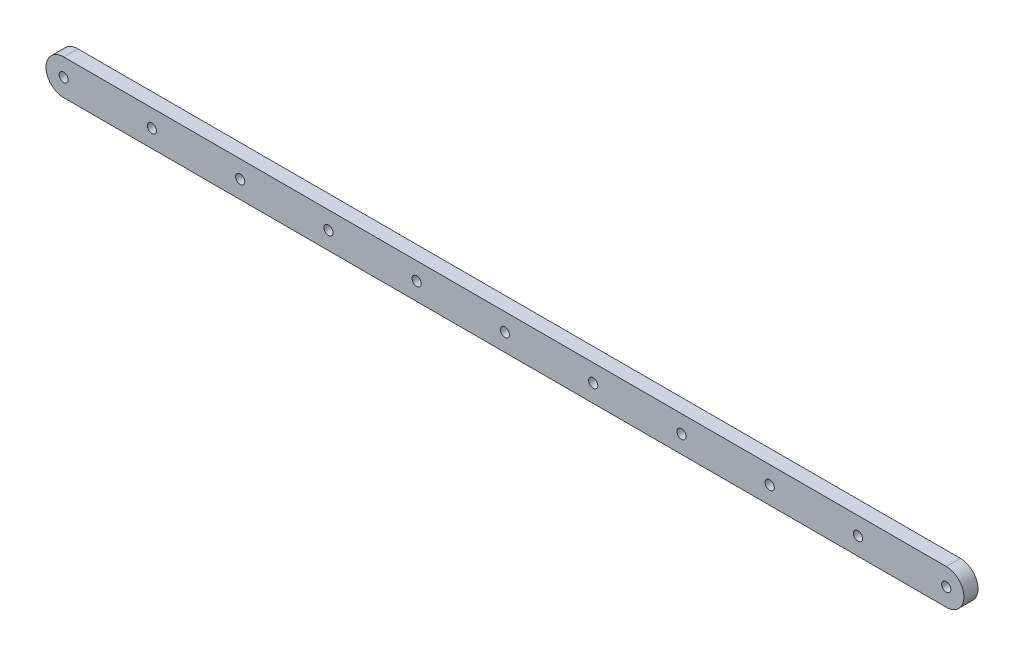
SolidWorks part; units mm, degrees
material "Pine"
ref_plane "Front Plane" through (0, 0, 0) normal (0, 0, 1) x (1, 0, 0)
ref_plane "Top Plane" through (0, 0, 0) normal (0, 1, 0) x (1, 0, 0)
ref_plane "Right Plane" through (0, 0, 0) normal (1, 0, 0) x (0, 0, -1)
sketch "Sketch1" plane through (0, 0, 0) normal (0, 0, 1) x (1, 0, 0)
  line L0 (0, 5) -> (250, 5)
  line L1 (250, -5) -> (0, -5)
  circle A0 centre (0, 0) radius 5
  circle A1 centre (250, 0) radius 5
  dimension "D1" = 250
  dimension "D2" = 10
extrude "Boss-Extrude1" add sketch "Sketch1" along normal blind 4 contours A1 L0 A0 L1 | A1 | A0
ref_plane "Plane1" through (0, 0, 2) normal (0, 0, 1) x (1, 0, 0)
sketch "Sketch2" plane through (0, 0, 4) normal (0, 0, 1) x (1, 0, 0)
  circle A0 centre (0, 0) radius 1.3
  circle A1 centre (250, 0) radius 1.3
  dimension "D1" = 2.6
extrude "Cut-Extrude1" cut sketch "Sketch2" against normal through all
pattern_linear "LPattern1" count 10 spacing 25 along (1, 0, 0) of "Cut-Extrude1"
